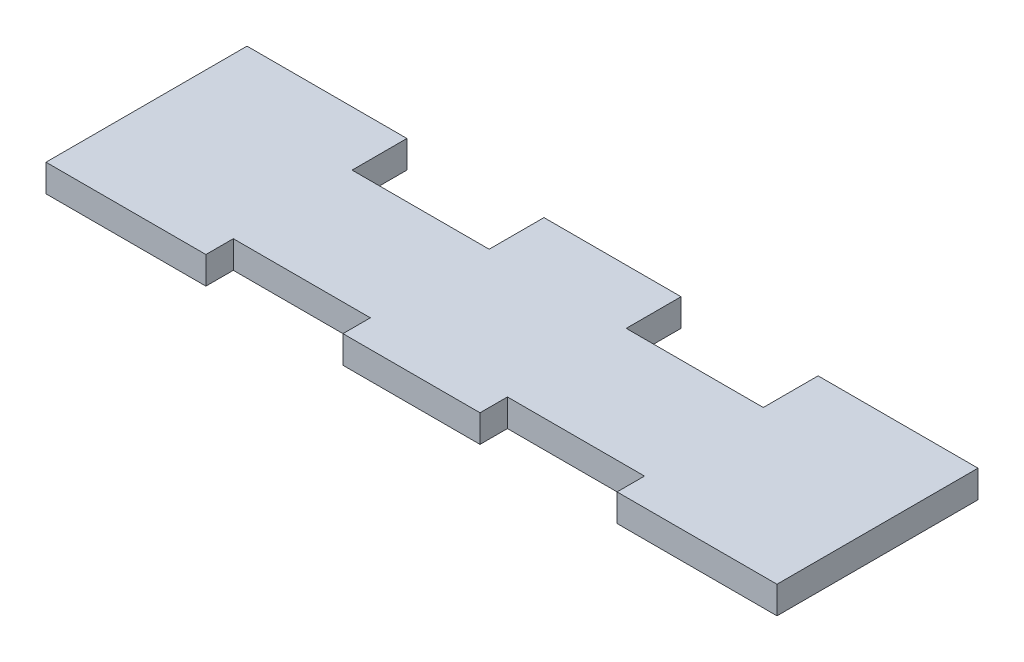
SolidWorks part; units mm, degrees
ref_plane "Alzado" through (0, 0, 0) normal (0, 0, 1) x (1, 0, 0)
ref_plane "Planta" through (0, 0, 0) normal (0, 1, 0) x (1, 0, 0)
ref_plane "Vista lateral" through (0, 0, 0) normal (1, 0, 0) x (0, 0, -1)
sketch "Croquis1" plane through (0, 0, 0) normal (0, 1, 0) x (1, 0, 0)
  line L0 (0, 0) -> (17.5, 0)
  line L1 (17.5, 0) -> (17.5, 3)
  line L2 (17.5, 3) -> (32.5, 3)
  line L3 (32.5, 3) -> (32.5, 0)
  line L4 (32.5, 0) -> (47.5, 0)
  line L5 (0, 0) -> (0, 22)
  line L6 (47.5, 3) -> (47.5, 0)
  line L7 (62.5, 3) -> (47.5, 3)
  line L8 (62.5, 0) -> (62.5, 3)
  line L9 (80, 0) -> (62.5, 0)
  line L10 (0, 22) -> (17.5, 22)
  line L11 (17.5, 22) -> (17.5, 16)
  line L12 (17.5, 16) -> (32.5, 16)
  line L13 (32.5, 16) -> (32.5, 22)
  line L14 (32.5, 22) -> (47.5, 22)
  line L15 (47.5, 22) -> (47.5, 16)
  line L16 (47.5, 16) -> (62.5, 16)
  line L17 (62.5, 16) -> (62.5, 22)
  line L18 (62.5, 22) -> (80, 22)
  line L19 (80, 22) -> (80, 0)
  dimension "D1" = 17.5
  dimension "D2" = 3
  dimension "D3" = 15
  dimension "D4" = 22
  dimension "D5" = 6
extrude "Saliente-Extruir1" add sketch "Croquis1" along normal blind 3
